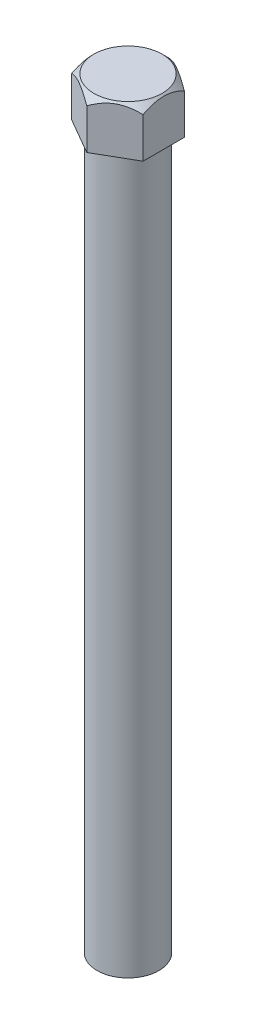
SolidWorks part; units mm, degrees
ref_plane "Front Plane" through (0, 0, 0) normal (0, 0, 1) x (1, 0, 0)
ref_plane "Top Plane" through (0, 0, 0) normal (0, 1, 0) x (1, 0, 0)
ref_plane "Right Plane" through (0, 0, 0) normal (1, 0, 0) x (0, 0, -1)
sketch "Sketch1" plane through (0, 0, 0) normal (0, 1, 0) x (1, 0, 0)
  circle A0 centre (0, 0) radius 0.13
  dimension "D1" = 0.26
extrude "Boss-Extrude1" add sketch "Sketch1" along normal blind 3
sketch "Sketch2" plane through (0, 3, 0) normal (0, 1, 0) x (1, 0, 0)
  line L0 (0, 0.1732) -> (0, -0.1732)
  line L1 (0, 0.1732) -> (-0.15, 0.0866)
  line L2 (-0.15, 0.0866) -> (-0.15, -0.0866)
  line L3 (-0.15, -0.0866) -> (0, -0.1732)
  line L4 (0, -0.1732) -> (0.15, -0.0866)
  line L5 (0.15, -0.0866) -> (0.15, 0.0866)
  line L6 (0.15, 0.0866) -> (0, 0.1732)
  circle A0 centre (0, 0) radius 0.15 construction
  circle M7 centre (0, 0) radius 0.13
  dimension "D1" = 0.3
extrude "Boss-Extrude2" add sketch "Sketch2" along normal blind 0.2 contours L5 L6 L0 L4 M7 | L0 M7 | L0 M7 | L2 L3 L0 L1 M7
sketch "Sketch4" plane through (0, 0, 0) normal (1, 0, 0) x (0, 0, -1)
  line L0 (0, 3.2) -> (0, 0) construction
  line L1 (-0.0866, 3.2) -> (0.0866, 3.2) construction
  line L2 (0.1432, 3.2) -> (0.1732, 3.2)
  line L3 (0.0866, 3.2) -> (0.1732, 3.2) construction
  line L4 (0.1732, 3.2) -> (0.1732, 3.17)
  line L5 (0.1732, 3.2) -> (0.1732, 3) construction
  line L6 (0.1732, 3.17) -> (0.1432, 3.2)
  dimension "D1" = 0.03
revolve "Cut-Revolve1" cut sketch "Sketch4" angle 360 about L0
